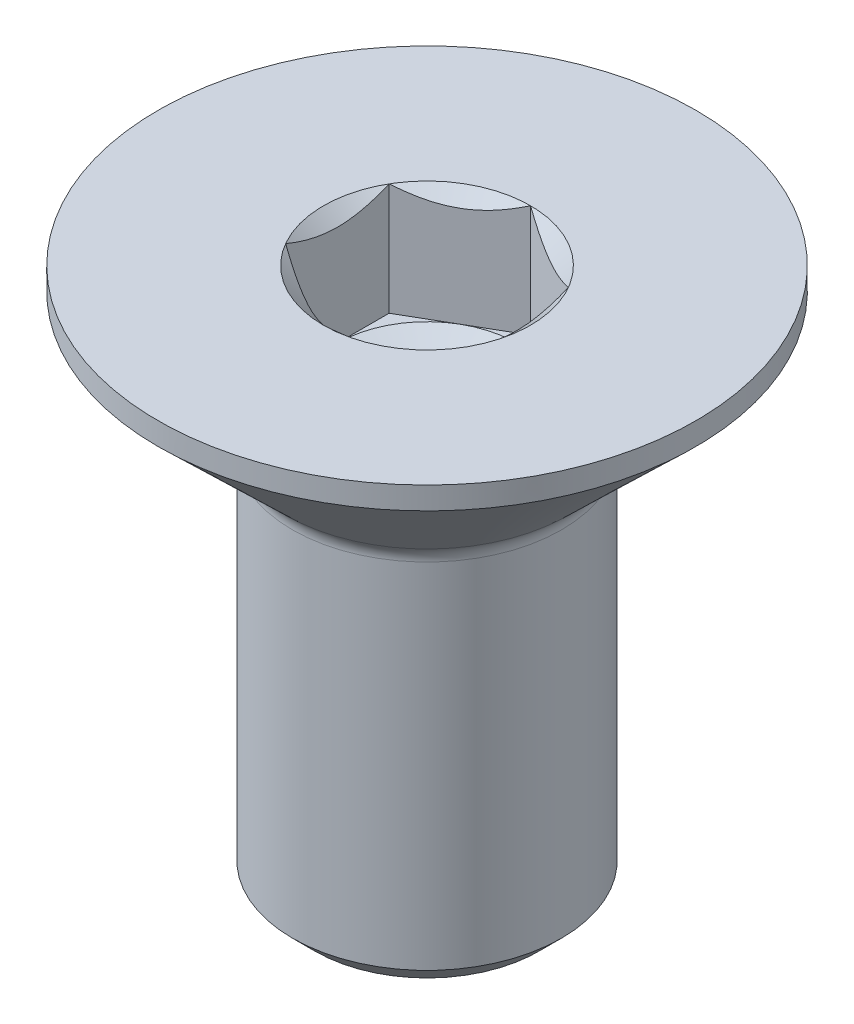
SolidWorks part; units mm, degrees
material "Galvanized Steel"
ref_plane "Front Plane" through (0, 0, 0) normal (0, 0, 1) x (1, 0, 0)
ref_plane "Top Plane" through (0, 0, 0) normal (0, 1, 0) x (1, 0, 0)
ref_plane "Right Plane" through (0, 0, 0) normal (1, 0, 0) x (0, 0, -1)
sketch "Sketch1" plane through (0, 0, 0) normal (0, 0, 1) x (1, 0, 0)
  line L0 (0, 0) -> (-6, 0)
  line L1 (-6, 0) -> (-6, -0.5)
  line L2 (-6, -0.5) -> (-3, -3.3971)
  line L3 (-3, -3.3971) -> (-3, -12)
  line L4 (-3, -12) -> (0, -12)
  line L5 (0, -12) -> (0, 0)
  line L6 (0, 0) -> (0, 13.0978) construction
  dimension "D1" = 46
  dimension "D2" = 6
  dimension "D3" = 12
  dimension "D4" = 0.5
  dimension "D5" = 12
revolve "Revolve1" add sketch "Sketch1" angle 360 about L6
sketch "Sketch2" plane through (0, 0, 0) normal (0, 1, 0) x (1, 0, 0)
  line L1 (0, 2.3094) -> (-2, 1.1547)
  line L2 (-2, 1.1547) -> (-2, -1.1547)
  line L3 (-2, -1.1547) -> (0, -2.3094)
  line L4 (0, -2.3094) -> (2, -1.1547)
  line L5 (2, -1.1547) -> (2, 1.1547)
  line L6 (2, 1.1547) -> (0, 2.3094)
  circle A0 centre (0, 0) radius 2 construction
  dimension "D1" = 4
extrude "Cut-Extrude1" cut sketch "Sketch2" against normal blind 2.5
sketch "Sketch3" plane through (0, 0, 0) normal (0, 0, 1) x (1, 0, 0)
  line L0 (-2.31, 0) -> (-2, -0.2601)
  line L1 (6, 0) -> (-6, 0) construction
  line L3 (-2, -0.2601) -> (-2, -2.5)
  line L4 (-2, -2.5) -> (0, -2.5) construction
  line L5 (-2, -2.5) -> (0, -3.2279)
  line L6 (0, -3.2279) -> (0, 0)
  line L7 (-2.31, 0) -> (0, 0)
  line L8 (0, -3.2279) -> (0, -12) construction
  line L9 (-3, -12) -> (3, -12) construction
  line L10 (-2, -2.5) -> (-2, 0) construction
  dimension "D1" = 4.62
  dimension "D2" = 40
  dimension "D3" = 20
revolve "Cut-Revolve1" cut sketch "Sketch3" angle 360 about L8
fillet "Fillet1" radius 0.5 1 edges at (0, -3.3971, -3)
chamfer "Chamfer1" distance 0.5 angle 45 1 edges at (0, -12, -3)
